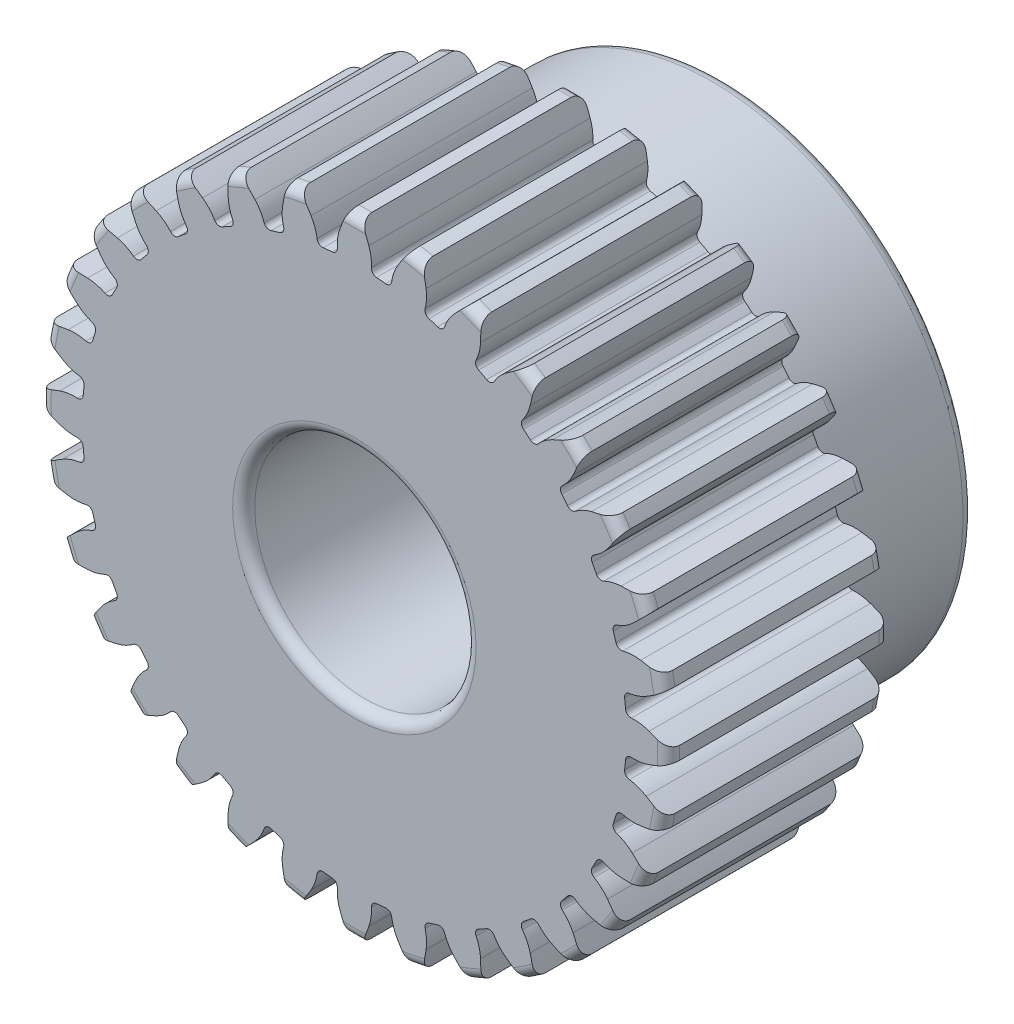
SolidWorks part; units mm, degrees
ref_plane "Front Plane" through (0, 0, 0) normal (0, 0, 1) x (1, 0, 0)
ref_plane "Top Plane" through (0, 0, 0) normal (0, 1, 0) x (1, 0, 0)
ref_plane "Right Plane" through (0, 0, 0) normal (1, 0, 0) x (0, 0, -1)
sketch "Sketch1" plane through (0, 0, 0) normal (0, 0, 1) x (1, 0, 0)
  line L0 (4.6553, 26.655) -> (5.8995, 26.4075)
  line L1 (-27.051, 0) -> (27.051, 0) construction
  line L2 (0, 27.051) -> (0, 25.4) construction
  line L3 (0, 25.4) -> (0, 23.4156) construction
  line L4 (-0.6343, 27.051) -> (0.6343, 27.051)
  line L5 (-0.6343, 27.051) -> (-1.9882, 23.3311)
  line L6 (0.6343, 27.051) -> (1.9882, 23.3311)
  line L7 (4.6553, 26.655) -> (2.6016, 23.2706)
  line L8 (-2.4936, -27.051) -> (2.4936, -27.051) construction
  line L9 (2.4936, -27.051) -> (0, -31.3701) construction
  line L10 (0, -31.3701) -> (-2.4936, -27.051) construction
  line L11 (0, -31.3701) -> (0, -31.1983) construction
  line L12 (-0.0992, -31.1983) -> (0.0992, -31.1983) construction
  line L13 (0, -27.2229) -> (0, -27.051) construction
  line L14 (5.2774, 26.5312) -> (0, 0) construction
  line L15 (2.3944, -27.2229) -> (-2.3944, -27.2229) construction
  line L16 (5.8995, 26.4075) -> (6.5017, 22.4949)
  line L17 (-2.444, -27.1369) -> (2.444, -27.1369) construction
  line L18 (0, 0) -> (-1.4675, 23.842) construction
  line L19 (0, 0) -> (3.2121, 23.6702) construction
  circle A0 centre (0, 0) radius 27.051
  circle A1 centre (0, 0) radius 25.4 construction
  circle A2 centre (0, 0) radius 9.525
  circle A3 centre (0, 0) radius 23.4156
  arc A4 (-1.2463, 25.3694) -> (1.2463, 25.3694) centre (0, 0) cw
  circle A5 centre (0, 0) radius 21.59 construction
  arc A6 (-1.9041, 23.3381) -> (-1.4675, 23.842) centre (-1.9428, 23.8128) ccw
  circle A8 centre (0, 0) radius 23.8125 construction
  arc A10 (-1.2463, 25.3694) -> (-1.4675, 23.842) centre (2.3112, 24.0746) ccw
  arc A11 (-0.5592, 27.051) -> (-1.2463, 25.3694) centre (20.7398, 17.3671) ccw
  arc A13 (2.6855, 23.2611) -> (3.2121, 23.6702) centre (2.7401, 23.7342) ccw
  arc A15 (3.727, 25.1251) -> (3.2121, 23.6702) centre (6.9635, 23.1611) ccw
  arc A16 (4.7289, 26.6403) -> (3.727, 25.1251) centre (23.7295, 12.9873) ccw
  arc A17 (1.9041, 23.3381) -> (1.4675, 23.842) centre (1.9428, 23.8128) cw
  arc A18 (1.2463, 25.3694) -> (1.4675, 23.842) centre (-2.3112, 24.0746) cw
  arc A19 (0.5592, 27.051) -> (1.2463, 25.3694) centre (-20.7398, 17.3671) cw
  arc A20 (6.4206, 22.5182) -> (6.0906, 23.0976) centre (6.5511, 22.9762) cw
  arc A21 (6.1717, 24.6388) -> (6.0906, 23.0976) centre (2.43, 24.0629) cw
  arc A22 (5.8259, 26.4221) -> (6.1717, 24.6388) centre (-16.9532, 21.0795) cw
  point P5 (0, 27.051)
  point P8 (5.2774, 26.5312)
  point P9 (10.352, 24.9919)
  point P10 (15.0287, 22.4921)
  point P11 (19.1279, 19.1279)
  point P12 (22.4921, 15.0287)
  point P13 (24.9919, 10.352)
  point P14 (26.5312, 5.2774)
  point P15 (27.051, 0)
  point P16 (26.5312, -5.2774)
  point P17 (24.9919, -10.352)
  point P18 (22.4921, -15.0287)
  point P19 (19.1279, -19.1279)
  point P20 (15.0287, -22.4921)
  point P21 (10.352, -24.9919)
  point P22 (0, 0)
  point P37 (-2.4936, -27.051)
  point P47 (0, -27.1369)
  point P48 (5.2774, -26.5312)
  point P49 (2.4936, -27.051)
  point P53 (7.4809, -27.051)
  point P54 (12.4682, -27.051)
  point P55 (17.4555, -27.051)
  point P56 (22.4428, -27.051)
  point P57 (27.4301, -27.051)
  point P58 (32.4174, -27.051)
  point P59 (37.4047, -27.051)
  point P60 (42.392, -27.051)
  point P61 (47.3793, -27.051)
  point P62 (52.3665, -27.051)
  point P63 (57.3538, -27.051)
  point P64 (62.3411, -27.051)
  point P65 (67.3284, -27.051)
  point P66 (72.3157, -27.051)
  point P69 (0, -27.051)
  point P70 (-5.2774, -26.5312)
  point P71 (-10.352, -24.9919)
  point P81 (0, 21.59)
  point P85 (-15.0287, -22.4921)
  point P86 (-19.1279, -19.1279)
  point P87 (-22.4921, -15.0287)
  point P89 (-24.9919, -10.352)
  point P90 (-26.5312, -5.2774)
  point P91 (-27.051, 0)
  point P92 (-26.5312, 5.2774)
  point P93 (-24.9919, 10.352)
  point P94 (-22.4921, 15.0287)
  point P109 (-19.1279, 19.1279)
  point P110 (-15.0287, 22.4921)
  point P111 (-10.352, 24.9919)
  point P112 (-5.2774, 26.5312)
  dimension "OD" = 54.102
  dimension "Shaft Diameter" = 19.05
  dimension "Pitch Diameter" = 50.8
  dimension "Hub Diameter" = 43.18
  dimension "D4" = 0.4762
  dimension "Driven Dim* Addendum (a)" = 1.651
  dimension "Dedendum (b)" = 1.9844
  dimension "D2" = 4.9873
  dimension "D3" = 0.1984
  dimension "Pressure Angle" = 20
  dimension "Clearance" = 0.3969
  dimension "D5" = 11.25
  dimension "D1" = 2.4936
  dimension "Gear Pitch" = 16
  dimension "Teeth" = 32
sketch "Sketch2" plane through (0, 0, 0) normal (1, 0, 0) x (0, 0, -1)
  line L0 (-15.875, 26.0985) -> (-15.875, -26.0985)
  line L1 (-14.9225, -27.051) -> (2.2225, -27.051)
  line L2 (3.175, -26.0985) -> (3.175, -22.5425)
  line L3 (4.1275, -21.59) -> (14.9225, -21.59)
  line L4 (15.875, -20.6375) -> (15.875, 20.6375)
  line L5 (14.9225, 21.59) -> (4.1275, 21.59)
  line L6 (3.175, 22.5425) -> (3.175, 26.0985)
  line L7 (2.2225, 27.051) -> (-14.9225, 27.051)
  line L8 (15.875, 0) -> (-15.875, 0) construction
  line L10 (3.175, 21.59) -> (-15.875, 21.59) construction
  line L13 (15.875, 9.525) -> (0, 9.525) construction
  line L15 (-15.875, 9.525) -> (0, 9.525) construction
  line L17 (15.875, -9.525) -> (0, -9.525) construction
  line L18 (0, -9.525) -> (-15.875, -9.525) construction
  arc A0 (-15.875, -26.0985) -> (-14.9225, -27.051) centre (-14.9225, -26.0985) ccw
  arc A1 (2.2225, -27.051) -> (3.175, -26.0985) centre (2.2225, -26.0985) ccw
  arc A2 (3.175, -22.5425) -> (4.1275, -21.59) centre (4.1275, -22.5425) cw
  arc A3 (15.875, -20.6375) -> (14.9225, -21.59) centre (14.9225, -20.6375) cw
  arc A4 (3.175, 22.5425) -> (4.1275, 21.59) centre (4.1275, 22.5425) ccw
  arc A5 (-15.875, 26.0985) -> (-14.9225, 27.051) centre (-14.9225, 26.0985) cw
  arc A6 (2.2225, 27.051) -> (3.175, 26.0985) centre (2.2225, 26.0985) cw
  arc A7 (14.9225, 21.59) -> (15.875, 20.6375) centre (14.9225, 20.6375) cw
  point P40 (15.875, 21.59)
  dimension "Radius" = 0.9525
  dimension "Hub Width" = 12.7
  dimension "Overall Width" = 31.75
sketch "Sketch3" plane through (0, 0, 0) normal (1, 0, 0) x (0, 0, -1)
  line L0 (14.9225, 9.525) -> (-14.9225, 9.525)
  line L1 (15.875, -20.6375) -> (15.875, 20.6375) construction
  line L2 (14.9225, 21.59) -> (4.1275, 21.59) construction
  line L3 (3.175, 22.5425) -> (3.175, 26.0985) construction
  line L4 (2.2225, 27.051) -> (-14.9225, 27.051) construction
  line L5 (-15.875, 26.0985) -> (-15.875, -26.0985) construction
  line L6 (15.875, 10.4775) -> (15.875, 20.6375)
  line L7 (14.9225, 21.59) -> (4.1275, 21.59)
  line L8 (3.175, 22.5425) -> (3.175, 26.0985)
  line L9 (2.2225, 27.051) -> (-14.9225, 27.051)
  line L10 (-15.875, 26.0985) -> (-15.875, 10.4775)
  line L11 (15.875, 9.525) -> (0, 9.525) construction
  arc A8 (15.875, 20.6375) -> (14.9225, 21.59) centre (14.9225, 20.6375) ccw construction
  arc A9 (3.175, 22.5425) -> (4.1275, 21.59) centre (4.1275, 22.5425) ccw construction
  arc A10 (3.175, 26.0985) -> (2.2225, 27.051) centre (2.2225, 26.0985) ccw construction
  arc A11 (-14.9225, 27.051) -> (-15.875, 26.0985) centre (-14.9225, 26.0985) ccw construction
  arc A12 (15.875, 20.6375) -> (14.9225, 21.59) centre (14.9225, 20.6375) ccw
  arc A13 (3.175, 22.5425) -> (4.1275, 21.59) centre (4.1275, 22.5425) ccw
  arc A14 (3.175, 26.0985) -> (2.2225, 27.051) centre (2.2225, 26.0985) ccw
  arc A15 (-14.9225, 27.051) -> (-15.875, 26.0985) centre (-14.9225, 26.0985) ccw
  arc A16 (-15.875, 10.4775) -> (-14.9225, 9.525) centre (-14.9225, 10.4775) ccw
  arc A17 (14.9225, 9.525) -> (15.875, 10.4775) centre (14.9225, 10.4775) ccw
revolve "Revolve1" add sketch "Sketch3" angle 360 about L8
sketch "Sketch4" plane through (0, 0, 15.875) normal (0, 0, 1) x (1, 0, 0)
  circle A9 centre (0, 0) radius 27.051 construction
  circle A21 centre (0, 0) radius 23.4156 construction
  arc A22 (2.6855, 23.2611) -> (3.2121, 23.6702) centre (2.7401, 23.7342) ccw construction
  arc A23 (3.727, 25.1251) -> (3.2121, 23.6702) centre (6.9635, 23.1611) ccw construction
  arc A24 (4.7289, 26.6403) -> (3.727, 25.1251) centre (23.7295, 12.9873) ccw construction
  arc A25 (1.2463, 25.3694) -> (0.5592, 27.051) centre (-20.7398, 17.3671) ccw construction
  arc A26 (1.4675, 23.842) -> (1.2463, 25.3694) centre (-2.3112, 24.0746) ccw construction
  arc A27 (1.4675, 23.842) -> (1.9041, 23.3381) centre (1.9428, 23.8128) ccw construction
  arc A28 (4.7252, 26.6351) -> (0.5619, 27.0452) centre (0, 0) ccw
  arc A29 (2.6855, 23.2611) -> (1.9041, 23.3381) centre (0, 0) ccw
  arc A30 (2.6855, 23.2611) -> (3.2121, 23.6702) centre (2.7401, 23.7342) ccw
  arc A31 (3.727, 25.1251) -> (3.2121, 23.6702) centre (6.9635, 23.1611) ccw
  arc A32 (4.7252, 26.6351) -> (3.727, 25.1251) centre (23.7295, 12.9873) ccw
  arc A33 (1.2463, 25.3694) -> (0.5619, 27.0452) centre (-20.7398, 17.3671) ccw
  arc A34 (1.4675, 23.842) -> (1.2463, 25.3694) centre (-2.3112, 24.0746) ccw
  arc A35 (1.4675, 23.842) -> (1.9041, 23.3381) centre (1.9428, 23.8128) ccw
extrude "Cut-Extrude1" cut sketch "Sketch4" against normal through all both and the other way through all
pattern_circular "CirPattern1" count 32 every 11.25 about axis through (0, 0, 0) along (0, 0, 1) of "Cut-Extrude1"
equation "\"D3@Sketch1\"=(1/\"Gear Pitch@Sketch1\")/8"
equation "\"D2@Sketch1\"=3.1416/\"Gear Pitch@Sketch1\""
equation "\"Dedendum (b)@Sketch1\"=1.25/\"Gear Pitch@Sketch1\""
equation "\"D1@Sketch1\"=1.5708/\"Gear Pitch@Sketch1\""
equation "\"D4@Sketch1\"=.3/\"Gear Pitch@Sketch1\""
equation "\"Clearance@Sketch1\" = .25 / \"Gear Pitch@Sketch1\""
equation "\"D1@CirPattern1\"=\"Teeth@Sketch1\""
equation "\"D5@Sketch1\"=360/\"Teeth@Sketch1\""
equation "\"D2@CirPattern1\"=\"D5@Sketch1\""
equation "\"Radius@Sketch2\"=.6/\"Gear Pitch@Sketch1\""
